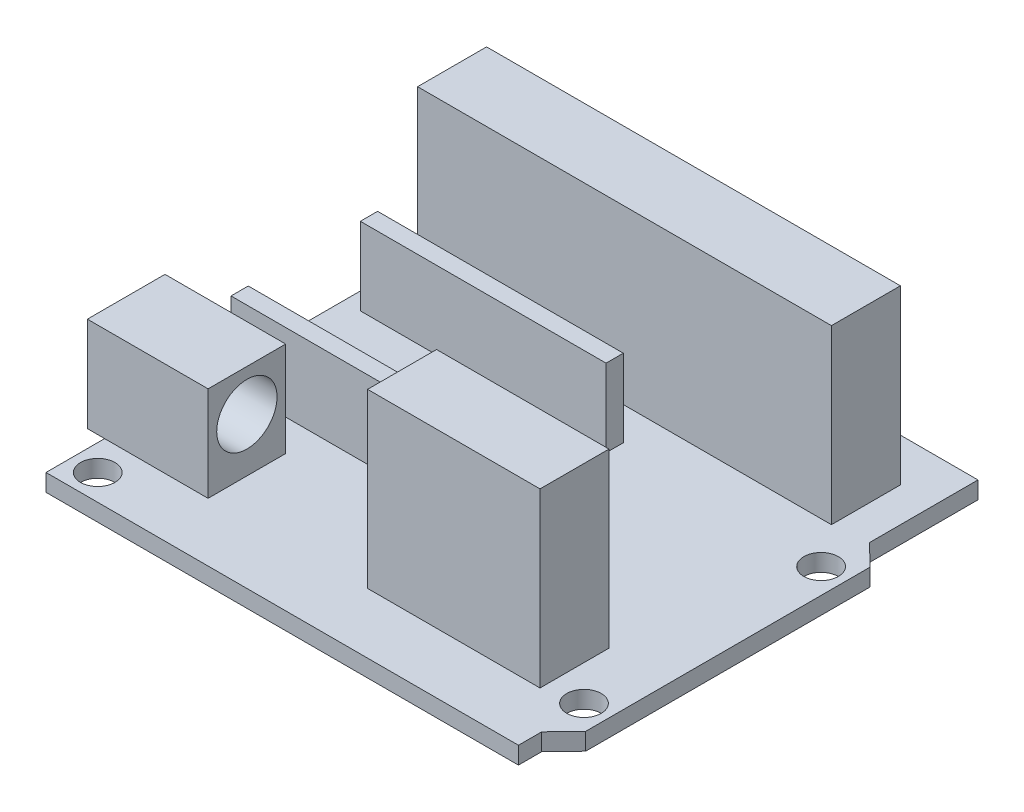
SolidWorks part; units mm, degrees
ref_plane "Front Plane" through (0, 0, 0) normal (0, 0, 1) x (1, 0, 0)
ref_plane "Top Plane" through (0, 0, 0) normal (0, 1, 0) x (1, 0, 0)
ref_plane "Right Plane" through (0, 0, 0) normal (1, 0, 0) x (0, 0, -1)
sketch "Sketch1" plane through (0, 0, 0) normal (0, 1, 0) x (1, 0, 0)
  line L0 (54.8, 53.3) -> (54.8, 40.7)
  line L1 (0, 0) -> (57.3, 0)
  line L2 (0, 0) -> (0, 53.3)
  line L3 (0, 53.3) -> (54.8, 53.3)
  line L4 (54.8, 40.7) -> (57.3, 38.3)
  line L5 (54.8, 0) -> (54.8, 2.6958)
  line L6 (0, 3) -> (3, 3) construction
  line L7 (3, 3) -> (3, 0) construction
  line L8 (54.8, 2.6958) -> (57.3, 5.3)
  line L9 (57.3, 5.3) -> (57.3, 0) construction
  line L10 (57.3, 38.3) -> (57.3, 5.3)
  line L11 (4, 53.3) -> (4, 50.8) construction
  line L12 (4, 50.8) -> (0, 50.8) construction
  line L13 (57.3, 8) -> (54.4, 8) construction
  line L14 (54.4, 8) -> (54.4, 10) construction
  line L15 (54.4, 8) -> (54.4, 0) construction
  line L16 (54.4, 35.5) -> (57.3, 35.5) construction
  line L17 (54.4, 35.5) -> (54.4, 53.3) construction
  circle A0 centre (3, 3) radius 2
  circle A1 centre (4, 50.8) radius 2
  circle A2 centre (54.4, 8) radius 2
  circle A3 centre (54.4, 35.5) radius 2
  point P19 (4, 50.8)
  point P20 (3, 3)
  point P30 (54.4, 35.5)
  point P31 (54.4, 8)
  dimension "D5" = 4
  dimension "D7" = 4
  dimension "D10" = 4
  dimension "D14" = 4
  dimension "D1" = 53.3
  dimension "D2" = 57.3
  dimension "D3" = 12.6
  dimension "D4" = 54.8
  dimension "D6" = 3
  dimension "D8" = 2.5
  dimension "D9" = 4
  dimension "D11" = 2.9
  dimension "D12" = 8
  dimension "D13" = 33
  dimension "D15" = 2.9
  dimension "D16" = 17.8
extrude "Boss-Extrude1" add sketch "Sketch1" along normal blind 2 contours L10 L4 L0 L3 L2 L1 L5 L8 A0
sketch "Sketch2" plane through (0, 2, 0) normal (0, 1, 0) x (1, 0, 0)
  line L0 (0, 34.4602) -> (2, 34.4602) construction
  line L1 (2, 36.4602) -> (30.5, 36.4602)
  line L2 (2, 36.4602) -> (2, 34.4602)
  line L3 (2, 34.4602) -> (30.5, 34.4602)
  line L4 (30.5, 36.4602) -> (30.5, 34.4602)
  line L5 (0, 0) -> (0, 53.3) construction
  dimension "D1" = 28.5
  dimension "D2" = 2
  dimension "D3" = 2
extrude "Boss-Extrude2" add sketch "Sketch2" along normal blind 9
pattern_linear "LPattern1" count 2 spacing 15 along (0, 0, 1) of "Boss-Extrude2"
sketch "Sketch3" plane through (0, 2, 0) normal (0, 1, 0) x (1, 0, 0)
  line L0 (57.3, 7) -> (50.3, 7) construction
  line L1 (57.3, 38.3) -> (57.3, 5.3) construction
  line L2 (50.3, 7) -> (50.3, 0) construction
  line L3 (0, 0) -> (54.8, 0) construction
  line L5 (50.3, 7) -> (30.3, 7)
  line L6 (50.3, 7) -> (50.3, 15)
  line L7 (50.3, 15) -> (30.3, 15)
  line L8 (30.3, 7) -> (30.3, 15)
  dimension "D1" = 7
  dimension "D2" = 7
  dimension "D3" = 20
  dimension "D4" = 8
extrude "Boss-Extrude3" add sketch "Sketch3" along normal blind 20
sketch "Sketch4" plane through (0, 2, 0) normal (0, 1, 0) x (1, 0, 0)
  line L0 (50.8, 53.3) -> (50.8, 48.3) construction
  line L1 (0, 53.3) -> (54.8, 53.3) construction
  line L2 (50.8, 48.3) -> (54.8, 48.3) construction
  line L3 (54.8, 53.3) -> (54.8, 40.7) construction
  line L5 (50.8, 48.3) -> (2.8, 48.3)
  line L6 (50.8, 48.3) -> (50.8, 40.3)
  line L7 (50.8, 40.3) -> (2.8, 40.3)
  line L8 (2.8, 48.3) -> (2.8, 40.3)
  dimension "D1" = 5
  dimension "D2" = 4
  dimension "D3" = 48
  dimension "D4" = 8
extrude "Boss-Extrude4" add sketch "Sketch4" along normal blind 20
ref_plane "Plane1" through (-2, 0, 0) normal (-1, 0, 0) x (0, 0, 1)
sketch "Sketch5" plane through (-2, 0, 0) normal (-1, 0, 0) x (0, 0, 1)
  line L0 (0, 2) -> (-53.3, 2) construction
  line L1 (-6.8, 2) -> (-15.8, 2)
  line L2 (-6.8, 2) -> (-6.8, 13)
  line L3 (-6.8, 13) -> (-15.8, 13)
  line L4 (-15.8, 2) -> (-15.8, 13)
  line L5 (0, 2) -> (-6.8, 2) construction
  line L6 (-11.3, 13) -> (-11.3, 8.2) construction
  circle A0 centre (-11.3, 8.2) radius 3.5
  dimension "D5" = 7
  dimension "D1" = 6.8
  dimension "D2" = 9
  dimension "D3" = 11
  dimension "D4" = 4.8
extrude "Boss-Extrude5" add sketch "Sketch5" against normal blind 14
